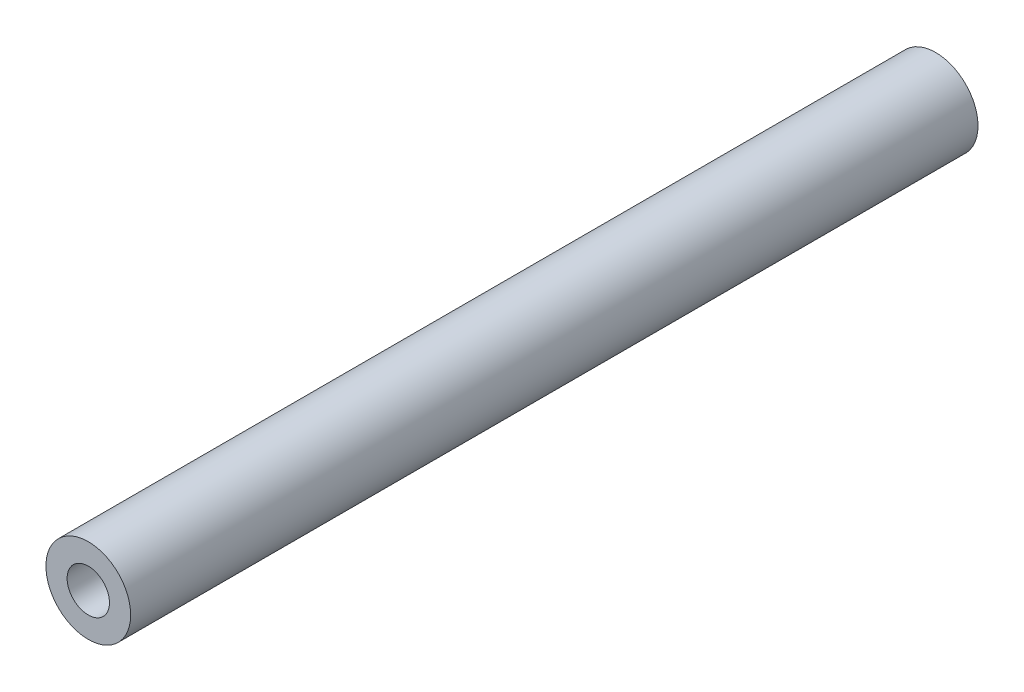
SolidWorks part; units mm, degrees
ref_plane "前视基准面" through (0, 0, 0) normal (0, 0, 1) x (1, 0, 0)
ref_plane "上视基准面" through (0, 0, 0) normal (0, 1, 0) x (1, 0, 0)
ref_plane "右视基准面" through (0, 0, 0) normal (1, 0, 0) x (0, 0, -1)
sketch "草图1" plane through (0, 0, 0) normal (0, 0, 1) x (1, 0, 0)
  circle A0 centre (0, 0) radius 3
  circle A1 centre (0, 0) radius 1.5
  dimension "D1" = 3
  dimension "D2" = 6
extrude "凸台-拉伸1" add sketch "草图1" along normal mid plane 60
